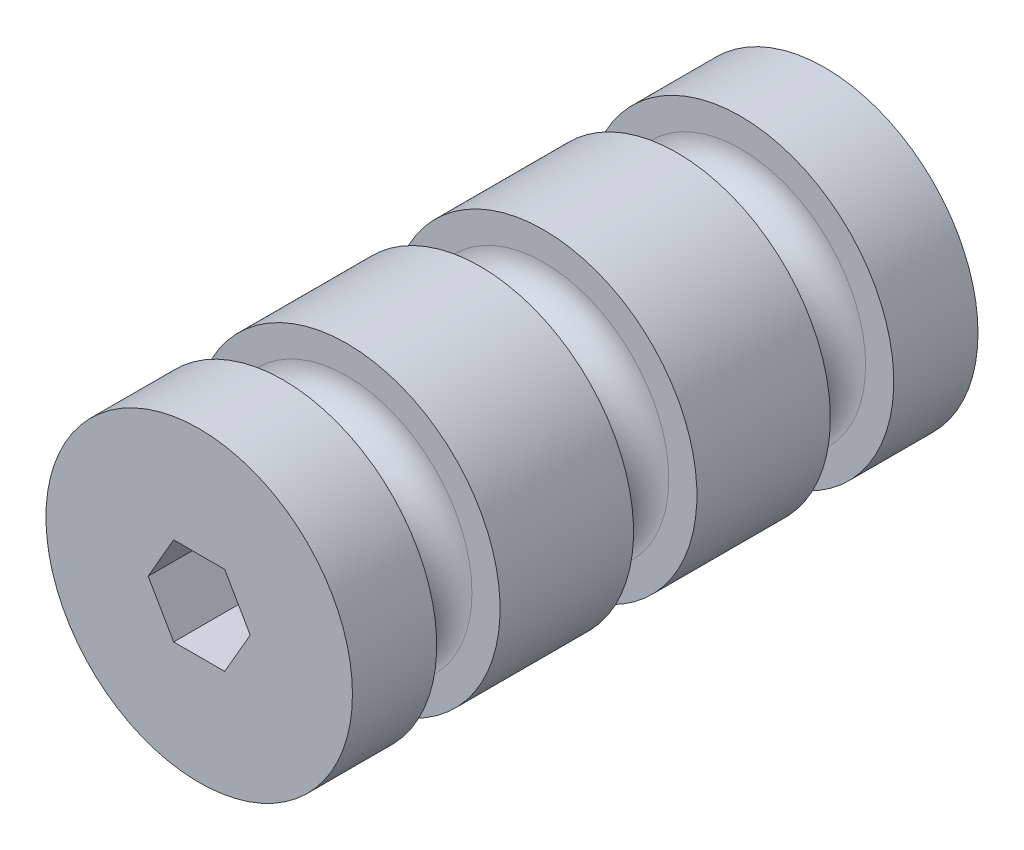
SolidWorks part; units mm, degrees
ref_plane "Front Plane" through (0, 0, 0) normal (0, 0, 1) x (1, 0, 0)
ref_plane "Top Plane" through (0, 0, 0) normal (0, 1, 0) x (1, 0, 0)
ref_plane "Right Plane" through (0, 0, 0) normal (1, 0, 0) x (0, 0, -1)
sketch "Sketch1" plane through (0, 0, 0) normal (0, 0, 1) x (1, 0, 0)
  line L0 (-3.8861, 6.731) -> (3.8861, 6.731)
  line L1 (3.8861, 6.731) -> (7.7723, 0)
  line L2 (7.7723, 0) -> (3.8861, -6.731)
  line L3 (3.8861, -6.731) -> (-3.8861, -6.731)
  line L4 (-3.8861, -6.731) -> (-7.7723, 0)
  line L5 (-7.7723, 0) -> (-3.8861, 6.731)
  line L6 (-7.7723, 0) -> (7.7723, 0) construction
  line L7 (-5.8292, -3.3655) -> (5.8292, 3.3655) construction
  line L8 (5.8292, -3.3655) -> (-5.8292, 3.3655) construction
  circle A0 centre (0, 0) radius 23.3362
  point P6 (0, 0)
  dimension "D1" = 46.6725
  dimension "D2" = 13.462
extrude "Boss-Extrude1" add sketch "Sketch1" along normal blind 95.25
sketch "Sketch2" plane through (0, 0, 0) normal (1, 0, 0) x (0, 0, -1)
  line L0 (0, 0) -> (-95.25, 0) construction
  line L5 (-82.423, 23.3362) -> (-72.771, 23.3362)
  line L8 (-82.423, 19.05) -> (-82.423, 23.3362)
  line L9 (-72.771, 19.05) -> (-72.771, 23.3362)
  line L10 (-52.451, 19.05) -> (-52.451, 23.3363)
  line L11 (-42.799, 19.05) -> (-42.799, 23.3363)
  line L12 (-22.479, 19.05) -> (-22.479, 23.3363)
  line L13 (-12.827, 19.05) -> (-12.827, 23.3363)
  line L14 (0, 23.3362) -> (-95.25, 23.3362) construction
  line L15 (-52.451, 23.3363) -> (-42.799, 23.3363)
  line L16 (-22.479, 23.3363) -> (-12.827, 23.3363)
  arc A3 (-82.423, 19.05) -> (-72.771, 19.05) centre (-77.597, 19.05) ccw
  arc A4 (-52.451, 19.05) -> (-42.799, 19.05) centre (-47.625, 19.05) ccw
  arc A5 (-22.479, 19.05) -> (-12.827, 19.05) centre (-17.653, 19.05) ccw
  point P4 (-22.479, 21.1931)
  point P13 (-47.625, 0)
  dimension "D1" = 4.2862
  dimension "D2" = 20.32
  dimension "D3" = 20.32
  dimension "D4" = 9.652
revolve "Cut-Revolve1" cut sketch "Sketch2" angle 360 about L0
